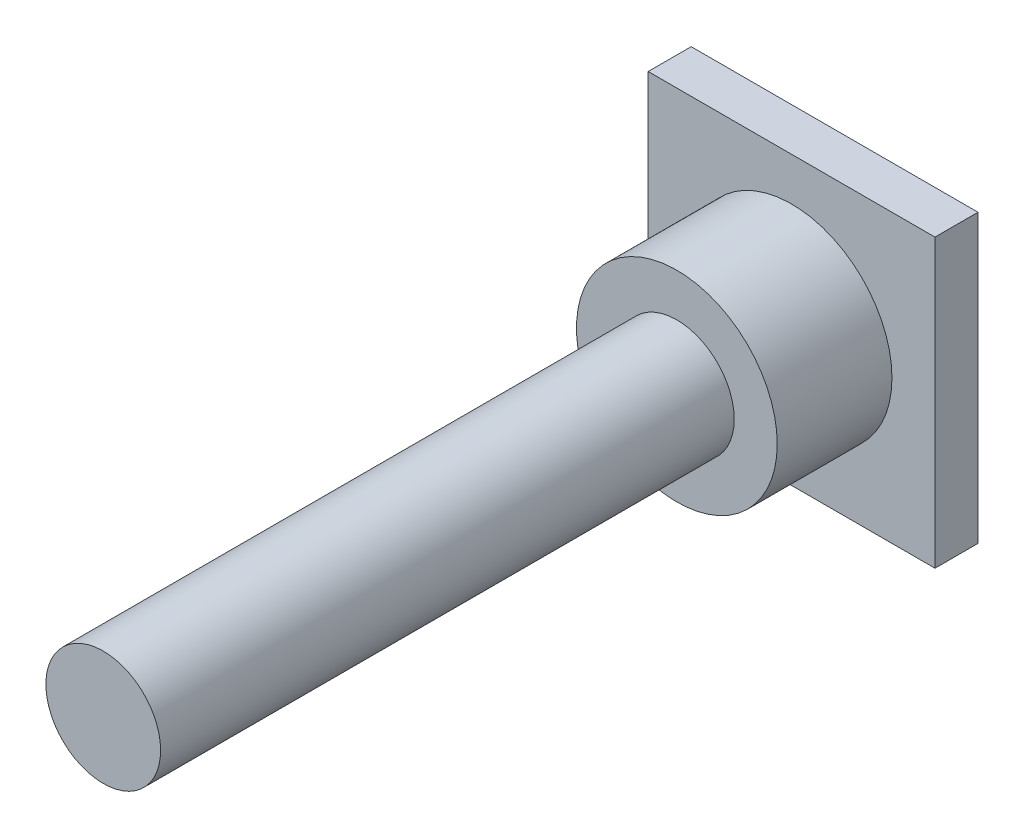
SolidWorks part; units mm, degrees
ref_plane "Plano frontal" through (0, 0, 0) normal (1, 0, 0) x (0, 1, 0)
ref_plane "Plano superior" through (0, 0, 0) normal (0, 0, 1) x (0, 1, 0)
ref_plane "Plano direito" through (0, 0, 0) normal (0, 1, 0) x (-1, 0, 0)
sketch "1_Base" plane through (0, 0, 0) normal (0, 0, 1) x (0, 1, 0)
  line L1 (-50, 50) -> (50, 50)
  line L2 (-50, 50) -> (-50, -50)
  line L3 (-50, -50) -> (50, -50)
  line L4 (50, 50) -> (50, -50)
  line L5 (-50, 50) -> (50, -50) construction
  line L6 (-50, -50) -> (50, 50) construction
  point P0 (0, 0)
  point P6 (-122.244, -50.2899)
  dimension "D1" = 100
  dimension "D2" = 100
extrude "Ressalto-extrusão1" add sketch "1_Base" along normal blind 15
sketch "2_Base_eixo" plane through (0, 0, 15) normal (0, 0, 1) x (1, 0, 0)
  line L0 (50, 50) -> (-50, 50) construction
  circle A0 centre (0, 0) radius 35
  dimension "D1" = 50
extrude "Ressalto-extrusão2" add sketch "2_Base_eixo" along normal blind 40
sketch "Esboço3" plane through (0, 0, 55) normal (0, 0, 1) x (1, 0, 0)
  circle A0 centre (0, 0) radius 20
extrude "Ressalto-extrusão3" add sketch "Esboço3" along normal blind 200
